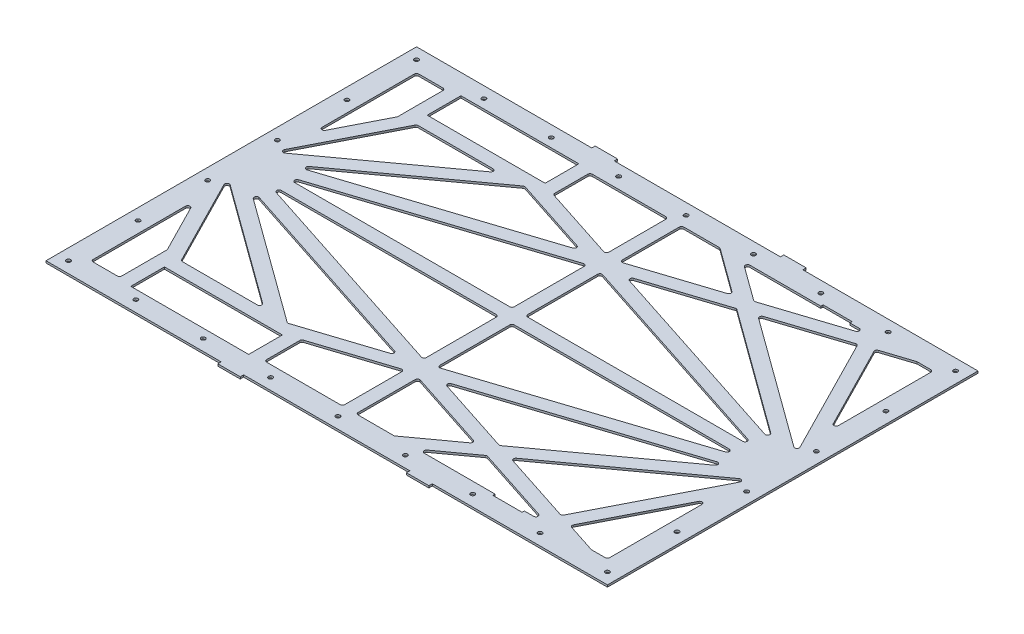
SolidWorks part; units mm, degrees
material "1060 Alloy"
ref_plane "Front Plane" through (0, 0, 0) normal (0, 0, 1) x (1, 0, 0)
ref_plane "Top Plane" through (0, 0, 0) normal (0, 1, 0) x (1, 0, 0)
ref_plane "Right Plane" through (0, 0, 0) normal (1, 0, 0) x (0, 0, -1)
sketch "Sketch1" plane through (0, 0, 0) normal (0, 1, 0) x (1, 0, 0)
  line L1 (-317.5, -209.55) -> (317.5, -209.55)
  line L2 (-317.5, -209.55) -> (-317.5, 209.55)
  line L3 (-317.5, 209.55) -> (317.5, 209.55)
  line L4 (317.5, -209.55) -> (317.5, 209.55)
  line L5 (-317.5, -209.55) -> (317.5, 209.55) construction
  line L6 (-317.5, 209.55) -> (317.5, -209.55) construction
  point P0 (0, 0)
  dimension "D1" = 635
  dimension "D2" = 419.1
extrude "Boss-Extrude1" add sketch "Sketch1" along normal blind 2.286
sketch "Sketch2" plane through (0, 2.286, 0) normal (0, 1, 0) x (1, 0, 0)
  line L0 (-317.5, -209.55) -> (317.5, -209.55) construction
  line L1 (-244.475, -148.59) -> (-111.125, -148.59)
  line L2 (-244.475, -148.59) -> (-244.475, -186.69)
  line L3 (-244.475, -186.69) -> (-111.125, -186.69)
  line L4 (-111.125, -148.59) -> (-111.125, -186.69)
  line L5 (-244.475, -148.59) -> (-111.125, -186.69) construction
  line L6 (-244.475, -186.69) -> (-111.125, -148.59) construction
  line L7 (-244.475, 186.69) -> (-111.125, 186.69)
  line L8 (-244.475, 186.69) -> (-244.475, 148.59)
  line L9 (-244.475, 148.59) -> (-111.125, 148.59)
  line L10 (-111.125, 186.69) -> (-111.125, 148.59)
  line L11 (-244.475, 186.69) -> (-111.125, 148.59) construction
  line L12 (-244.475, 148.59) -> (-111.125, 186.69) construction
  line L25 (317.5, 209.55) -> (-317.5, 209.55) construction
  point P0 (-177.8, -167.64)
  point P5 (-177.8, 167.64)
  dimension "D1" = 22.86
  dimension "D2" = 22.86
  dimension "D4" = 177.8
  dimension "D5" = 38.1
  dimension "D6" = 133.35
extrude "Cut-Extrude1" cut sketch "Sketch2" against normal through all
sketch "Sketch3" plane through (0, 2.286, 0) normal (0, 1, 0) x (1, 0, 0)
  line L0 (-317.5, 0) -> (317.5, 0) construction
  line L1 (-317.5, 209.55) -> (-317.5, -209.55) construction
  line L2 (317.5, -209.55) -> (317.5, 209.55) construction
  line L3 (-317.5, 0) -> (508.1387, 268.2663) construction
  line L5 (-317.5, 0) -> (333.1681, -211.4149) construction
  line L6 (-317.5, 0) -> (171.0241, -354.9336) construction
  line L7 (317.5, 0) -> (-424.9586, 241.2394) construction
  line L8 (317.5, 0) -> (-148.2716, 338.4029) construction
  line L9 (317.5, 0) -> (-385.7666, -228.5052) construction
  line L10 (317.5, 0) -> (-95.6882, -300.1988) construction
  line L11 (-43.3796, 0) -> (43.3796, 0) construction
  line L12 (-317.5, 0) -> (507.2449, 599.2123) construction
  line L16 (-321.9789, -6.1647) -> (166.5452, -361.0983) construction
  line L17 (-319.8547, -7.2471) -> (330.8134, -218.6619) construction
  line L18 (-317.5, -7.62) -> (317.5, -7.62) construction
  line L19 (-315.1453, -7.2471) -> (510.4934, 261.0192) construction
  line L20 (292.1, -184.15) -> (292.1, 184.15)
  line L21 (292.1, 184.15) -> (-292.1, 184.15)
  line L22 (-292.1, 184.15) -> (-292.1, -184.15)
  line L23 (-292.1, -184.15) -> (292.1, -184.15)
  line L24 (292.1, -184.15) -> (292.1, 184.15) construction
  line L25 (292.1, 184.15) -> (-292.1, 184.15) construction
  line L26 (-292.1, 184.15) -> (-292.1, -184.15) construction
  line L27 (-292.1, -184.15) -> (292.1, -184.15) construction
  line L28 (-313.0211, -6.1647) -> (511.7239, 593.0476) construction
  line L29 (319.8547, 7.2471) -> (-422.6039, 248.4865) construction
  line L30 (315.1453, 7.2471) -> (-388.1213, -221.2581) construction
  line L31 (313.0211, 6.1647) -> (-100.1672, -294.0341) construction
  line L32 (321.9789, 6.1647) -> (-143.7926, 344.5676) construction
  line L33 (-313.0211, 6.1647) -> (175.5031, -348.7689) construction
  line L34 (-315.1453, 7.2471) -> (335.5228, -204.1678) construction
  line L35 (-317.5, 7.62) -> (317.5, 7.62) construction
  line L36 (-319.8547, 7.2471) -> (505.784, 275.5133) construction
  line L37 (-321.9789, 6.1647) -> (502.766, 605.377) construction
  line L38 (315.1453, -7.2471) -> (-427.3133, 233.9924) construction
  line L39 (319.8547, -7.2471) -> (-383.4119, -235.7522) construction
  line L40 (321.9789, -6.1647) -> (-91.2093, -306.3635) construction
  line L41 (313.0211, -6.1647) -> (-152.7505, 332.2381) construction
  line L42 (0, 209.55) -> (0, -209.55) construction
  line L43 (317.5, 209.55) -> (-317.5, 209.55) construction
  line L44 (-317.5, -209.55) -> (317.5, -209.55) construction
  line L45 (-7.62, 209.55) -> (-7.62, -209.55) construction
  line L46 (7.62, 209.55) -> (7.62, -209.55) construction
  line L88 (-259.715, -133.35) -> (-259.715, -186.69)
  line L89 (-95.885, -133.35) -> (-259.715, -133.35)
  line L90 (-95.885, -186.69) -> (-95.885, -133.35)
  line L91 (-259.715, -133.35) -> (-259.715, -186.69) construction
  line L92 (-95.885, -133.35) -> (-259.715, -133.35) construction
  line L93 (-95.885, -186.69) -> (-95.885, -133.35) construction
  line L100 (-95.885, 133.35) -> (-95.885, 186.69)
  line L101 (-259.715, 133.35) -> (-95.885, 133.35)
  line L102 (-259.715, 186.69) -> (-259.715, 133.35)
  line L103 (-95.885, 133.35) -> (-95.885, 186.69) construction
  line L104 (-259.715, 133.35) -> (-95.885, 133.35) construction
  line L105 (-259.715, 186.69) -> (-259.715, 133.35) construction
  line L125 (-317.5, 0) -> (36.7641, 695.2825) construction
  line L126 (-317.5, 0) -> (-16.7714, -590.2131) construction
  line L151 (317.5, 0) -> (44.5098, 535.7735) construction
  line L152 (317.5, 0) -> (71.1855, -483.4194) construction
  line L153 (-326.0521, 0) -> (29.9747, 698.7419) construction
  line L154 (-326.0521, 0) -> (-23.5609, -593.6725) construction
  line L155 (326.0521, 0) -> (77.975, -486.8788) construction
  line L166 (326.0521, 0) -> (51.2993, 539.2329) construction
  line L167 (-308.9479, 0) -> (43.5536, 691.8231) construction
  line L168 (-308.9479, 0) -> (-9.9819, -586.7537) construction
  line L169 (308.9479, 0) -> (64.3961, -479.96) construction
  line L170 (308.9479, 0) -> (37.7203, 532.314) construction
  dimension "D1" = 36
  dimension "D2" = 18
  dimension "D3" = 18
  dimension "D4" = 36
  dimension "D5" = 18
  dimension "D6" = 18
  dimension "D7" = 36
  dimension "D8" = 36
  dimension "D17" = 63
  dimension "D19" = 63
  dimension "D20" = 63
  dimension "D21" = 63
  dimension "D9" = 25.4
  dimension "D10" = 7.62
  dimension "D11" = 7.62
  dimension "D12" = 7.62
  dimension "D13" = 7.62
  dimension "D14" = 15.24
  dimension "D15" = 15.24
  dimension "D22" = 7.62
  dimension "D23" = 7.62
sketch "Sketch4" plane through (0, 2.286, 0) normal (0, 1, 0) x (1, 0, 0)
  line L0 (-292.1, -184.15) -> (292.1, -184.15) construction
  line L1 (-259.715, -133.35) -> (-259.715, -186.69) construction
  line L2 (-292.1, 184.15) -> (-292.1, -184.15) construction
  line L3 (-326.0521, 0) -> (-23.5609, -593.6725) construction
  line L4 (-289.56, -184.15) -> (-262.255, -184.15)
  line L5 (-259.715, -130.8037) -> (-259.715, -181.61)
  line L6 (-292.1, -77.2147) -> (-292.1, -181.61)
  line L7 (-287.2968, -76.0615) -> (-259.9918, -129.6506)
  line L8 (-95.885, -133.35) -> (-259.715, -133.35) construction
  line L9 (-321.9789, -6.1647) -> (166.5452, -361.0983) construction
  line L10 (-308.9479, 0) -> (-9.9819, -586.7537) construction
  line L11 (-154.7407, -133.35) -> (-239.4461, -133.35)
  line L12 (-287.7418, -31.0395) -> (-153.2477, -128.7551)
  line L13 (-291.4979, -34.2475) -> (-241.7093, -131.9631)
  line L14 (315.1453, 7.2471) -> (-388.1213, -221.2581) construction
  line L15 (-319.8547, -7.2471) -> (330.8134, -218.6619) construction
  line L16 (-313.0211, 6.1647) -> (175.5031, -348.7689) construction
  line L17 (-32.0935, -105.5777) -> (-118.7055, -133.7196)
  line L18 (-258.8466, -27.0698) -> (-32.0935, -100.7463)
  line L19 (-261.1245, -31.5404) -> (-120.9834, -133.3588)
  line L20 (-7.62, 209.55) -> (-7.62, -209.55) construction
  line L21 (-317.5, -7.62) -> (317.5, -7.62) construction
  line L22 (-315.1453, 7.2471) -> (335.5228, -204.1678) construction
  line L23 (-7.62, -10.16) -> (-7.62, -89.178)
  line L24 (-253.3523, -7.62) -> (-10.16, -7.62)
  line L25 (-254.1372, -12.5757) -> (-10.9449, -91.5936)
  line L26 (319.8547, -7.2471) -> (-383.4119, -235.7522) construction
  line L27 (-95.885, -186.69) -> (-95.885, -133.35) construction
  line L28 (-93.345, -184.15) -> (-10.16, -184.15)
  line L29 (-7.62, -117.146) -> (-7.62, -181.61)
  line L30 (-10.9449, -114.7304) -> (-94.1299, -141.7588)
  line L31 (-95.885, -181.61) -> (-95.885, -144.1745)
  line L32 (-317.5, 0) -> (317.5, 0) construction
  line L33 (0, 209.55) -> (0, -209.55) construction
  line L34 (-317.5, 0) -> (317.5, 0) construction
  line L35 (0, 209.55) -> (0, -209.55) construction
  line L36 (254.1372, -12.5757) -> (10.9449, -91.5936)
  line L37 (253.3523, -7.62) -> (10.16, -7.62)
  line L38 (7.62, -10.16) -> (7.62, -89.178)
  line L39 (261.1245, -31.5404) -> (120.9834, -133.3588)
  line L40 (258.8466, -27.0698) -> (32.0935, -100.7463)
  line L41 (32.0935, -105.5777) -> (118.7055, -133.7196)
  line L42 (308.9479, 0) -> (64.3961, -479.96) construction
  line L43 (287.7418, -31.0395) -> (141.885, -137.0106)
  line L44 (142.5931, -141.4812) -> (221.4069, -167.0893)
  line L45 (321.9789, -6.1647) -> (-91.2093, -306.3635) construction
  line L46 (313.0211, 6.1647) -> (-100.1672, -294.0341) construction
  line L47 (7.62, 209.55) -> (7.62, -209.55) construction
  line L48 (121.565, -151.7739) -> (83.3275, -179.5551)
  line L49 (10.9449, -114.7304) -> (99.9553, -143.6516)
  line L50 (100.6634, -148.1222) -> (51.743, -183.6649)
  line L51 (10.16, -184.15) -> (50.2501, -184.15)
  line L52 (7.62, -117.146) -> (7.62, -181.61)
  line L53 (84.8205, -184.15) -> (208.5597, -184.15)
  line L54 (123.8429, -151.4131) -> (209.3446, -179.1943)
  line L55 (292.1, -184.15) -> (292.1, 184.15) construction
  line L56 (326.0521, 0) -> (77.975, -486.8788) construction
  line L57 (291.4979, -34.2475) -> (224.4549, -165.8268)
  line L58 (292.1, -181.61) -> (292.1, -77.2147)
  line L59 (287.2968, -76.0615) -> (239.495, -169.878)
  line L60 (240.9732, -173.4468) -> (273.5317, -184.0257)
  line L61 (274.3166, -184.15) -> (289.56, -184.15)
  arc A0 (-120.9834, -133.3588) -> (-118.7055, -133.7196) centre (-119.4904, -131.3039) ccw
  arc A1 (-32.0935, -105.5777) -> (-32.0935, -100.7463) centre (-32.8785, -103.162) ccw
  arc A2 (-261.1245, -31.5404) -> (-258.8466, -27.0698) centre (-259.6315, -29.4855) cw
  arc A3 (-259.715, -181.61) -> (-262.255, -184.15) centre (-262.255, -181.61) cw
  arc A4 (-289.56, -184.15) -> (-292.1, -181.61) centre (-289.56, -181.61) cw
  arc A5 (-292.1, -77.2147) -> (-287.2968, -76.0615) centre (-289.56, -77.2147) cw
  arc A6 (-259.9918, -129.6506) -> (-259.715, -130.8037) centre (-262.255, -130.8037) cw
  arc A7 (-239.4461, -133.35) -> (-241.7093, -131.9631) centre (-239.4461, -130.81) cw
  arc A8 (-153.2477, -128.7551) -> (-154.7407, -133.35) centre (-154.7407, -130.81) cw
  arc A9 (-287.7418, -31.0395) -> (-291.4979, -34.2475) centre (-289.2347, -33.0944) ccw
  arc A10 (-10.9449, -91.5936) -> (-7.62, -89.178) centre (-10.16, -89.178) ccw
  arc A11 (-7.62, -10.16) -> (-10.16, -7.62) centre (-10.16, -10.16) ccw
  arc A12 (-253.3523, -7.62) -> (-254.1372, -12.5757) centre (-253.3523, -10.16) ccw
  arc A13 (-95.885, -181.61) -> (-93.345, -184.15) centre (-93.345, -181.61) ccw
  arc A14 (-10.16, -184.15) -> (-7.62, -181.61) centre (-10.16, -181.61) ccw
  arc A15 (-10.9449, -114.7304) -> (-7.62, -117.146) centre (-10.16, -117.146) cw
  arc A16 (-94.1299, -141.7588) -> (-95.885, -144.1745) centre (-93.345, -144.1745) ccw
  arc A17 (253.3523, -7.62) -> (254.1372, -12.5757) centre (253.3523, -10.16) cw
  arc A18 (7.62, -10.16) -> (10.16, -7.62) centre (10.16, -10.16) cw
  arc A19 (10.9449, -91.5936) -> (7.62, -89.178) centre (10.16, -89.178) cw
  arc A20 (287.7418, -31.0395) -> (291.4979, -34.2475) centre (289.2347, -33.0944) cw
  arc A21 (142.5931, -141.4812) -> (141.885, -137.0106) centre (143.378, -139.0655) cw
  arc A22 (221.4069, -167.0893) -> (224.4549, -165.8268) centre (222.1918, -164.6736) ccw
  arc A23 (261.1245, -31.5404) -> (258.8466, -27.0698) centre (259.6315, -29.4855) ccw
  arc A24 (32.0935, -105.5777) -> (32.0935, -100.7463) centre (32.8785, -103.162) cw
  arc A25 (120.9834, -133.3588) -> (118.7055, -133.7196) centre (119.4904, -131.3039) cw
  arc A26 (99.9553, -143.6516) -> (100.6634, -148.1222) centre (99.1704, -146.0673) cw
  arc A27 (50.2501, -184.15) -> (51.743, -183.6649) centre (50.2501, -181.61) ccw
  arc A28 (10.16, -184.15) -> (7.62, -181.61) centre (10.16, -181.61) cw
  arc A29 (7.62, -117.146) -> (10.9449, -114.7304) centre (10.16, -117.146) cw
  arc A30 (209.3446, -179.1943) -> (208.5597, -184.15) centre (208.5597, -181.61) cw
  arc A31 (84.8205, -184.15) -> (83.3275, -179.5551) centre (84.8205, -181.61) cw
  arc A32 (121.565, -151.7739) -> (123.8429, -151.4131) centre (123.058, -153.8288) cw
  arc A33 (287.2968, -76.0615) -> (292.1, -77.2147) centre (289.56, -77.2147) cw
  arc A34 (292.1, -181.61) -> (289.56, -184.15) centre (289.56, -181.61) cw
  arc A35 (274.3166, -184.15) -> (273.5317, -184.0257) centre (274.3166, -181.61) cw
  arc A36 (240.9732, -173.4468) -> (239.495, -169.878) centre (241.7581, -171.0311) cw
  dimension "D1" = 2.54
  dimension "D2" = 2.54
  dimension "D3" = 2.54
  dimension "D4" = 2.54
  dimension "D5" = 2.54
  dimension "D6" = 2.54
  dimension "D7" = 2.54
  dimension "D8" = 2.54
  dimension "D9" = 2.54
extrude "Cut-Extrude2" cut sketch "Sketch4" against normal through all
sketch "Sketch5" plane through (0, 2.286, 0) normal (0, 1, 0) x (1, 0, 0)
  line L0 (84.8205, -184.15) -> (208.5597, -184.15) construction
  line L1 (198.12, -184.15) -> (165.1, -184.15)
  line L2 (198.12, -184.15) -> (198.12, -186.69)
  line L3 (198.12, -186.69) -> (165.1, -186.69)
  line L4 (165.1, -184.15) -> (165.1, -186.69)
  line L5 (-244.475, -186.69) -> (-111.125, -186.69) construction
  line L6 (317.5, -209.55) -> (317.5, 209.55) construction
  dimension "D1" = 33.02
  dimension "D2" = 119.38
extrude "Cut-Extrude3" cut sketch "Sketch5" against normal blind 2.54
mirror "Mirror1" about plane through (0, 0, 0) normal (0, 0, 1) of "Cut-Extrude3", "Cut-Extrude2"
sketch "Sketch8" plane through (0, 2.286, 0) normal (0, 1, 0) x (1, 0, 0)
  line L0 (317.5, 209.55) -> (-317.5, 209.55) construction
  line L1 (-93.98, 209.55) -> (-119.38, 209.55)
  line L2 (-93.98, 209.55) -> (-93.98, 213.36)
  line L3 (-93.98, 213.36) -> (-119.38, 213.36)
  line L4 (-119.38, 209.55) -> (-119.38, 213.36)
  line L5 (-317.5, 209.55) -> (-317.5, -209.55) construction
  point P6 (-106.68, 213.36)
  dimension "D1" = 3.81
  dimension "D2" = 210.82
  dimension "D3" = 25.4
extrude "Boss-Extrude3" add sketch "Sketch8" against normal up to surface (2.286 mm away) up to face at (155.8304, 0, 177.2521)
mirror "Mirror4" about plane through (0, 0, 0) normal (1, 0, 0) of "Boss-Extrude3"
mirror "Mirror5" about plane through (0, 0, 0) normal (0, 0, 1) of "Mirror4", "Boss-Extrude3"
sketch "Sketch9" plane through (0, 2.286, 0) normal (0, 1, 0) x (1, 0, 0)
  line L0 (-317.5, -209.55) -> (-119.38, -209.55) construction
  line L1 (-317.5, 209.55) -> (-317.5, -209.55) construction
  circle A0 centre (-304.8, -196.85) radius 2.3813
  dimension "D1" = 4.7625
  dimension "D2" = 12.7
  dimension "D3" = 12.7
extrude "Cut-Extrude5" cut sketch "Sketch9" against normal blind 2.54
pattern_linear "LPattern1" count 9 spacing 76.2 along (1, 0, 0) of "Cut-Extrude5"
pattern_linear "LPattern2" count 9 spacing 78.74 along (0, 0, -1) of "Cut-Extrude5"
mirror "Mirror6" about plane through (0, 0, 0) normal (1, 0, 0) of "LPattern2"
mirror "Mirror7" about plane through (0, 0, 0) normal (0, 0, 1) of "LPattern1"
